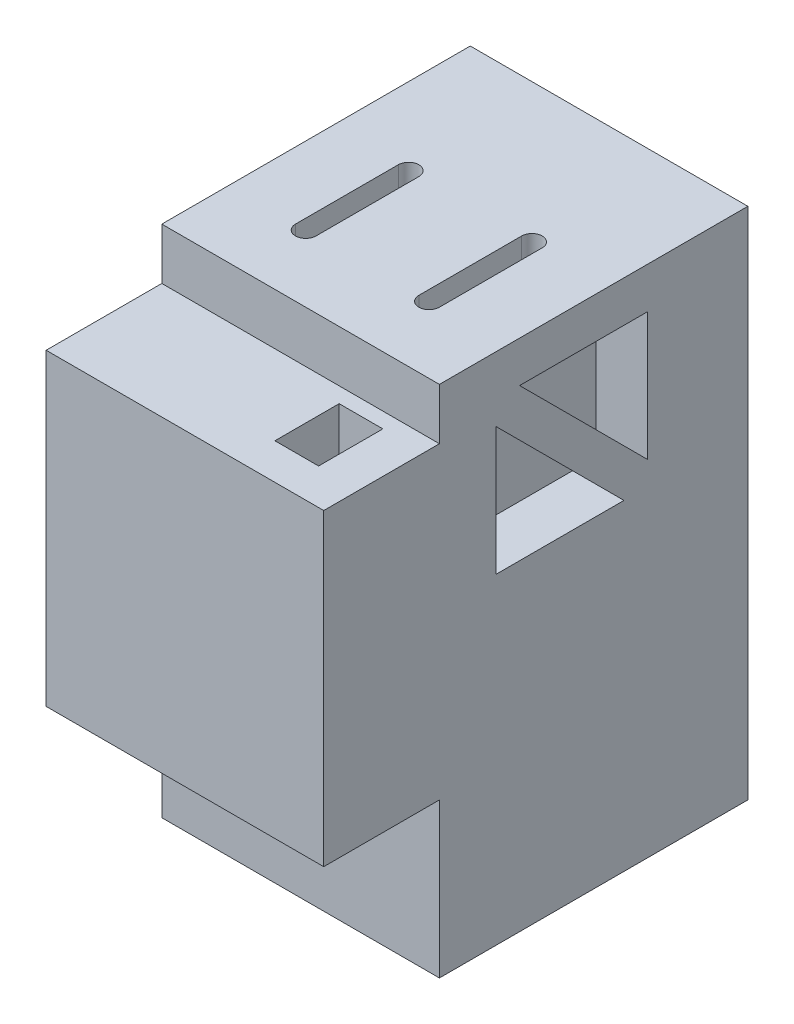
SolidWorks part; units mm, degrees
ref_plane "前视基准面" through (0, 0, 0) normal (0, 0, 1) x (1, 0, 0)
ref_plane "上视基准面" through (0, 0, 0) normal (0, 1, 0) x (1, 0, 0)
ref_plane "右视基准面" through (0, 0, 0) normal (1, 0, 0) x (0, 0, -1)
sketch "草图1" plane through (0, 0, 0) normal (0, 0, 1) x (1, 0, 0)
  line L0 (-54, 0) -> (0, 0)
  line L1 (0, 0) -> (0, -100)
  line L2 (-54, 0) -> (-54, -100)
  line L3 (-54, -100) -> (0, -100)
  dimension "D1" = 54
  dimension "D2" = 100
extrude "凸台-拉伸1" add sketch "草图1" along normal blind 60
sketch "草图2" plane through (0, 0, 60) normal (0, 0, 1) x (1, 0, 0)
  line L0 (-54, -10) -> (0, -10)
  line L1 (-54, 0) -> (-54, -100) construction
  line L2 (0, -100) -> (0, 0) construction
  line L3 (0, -10) -> (0, -70)
  line L4 (0, -70) -> (-54, -70)
  line L5 (-54, -70) -> (-54, -10)
  line L6 (0, 0) -> (-54, 0) construction
  dimension "D1" = 10
  dimension "D2" = 60
extrude "凸台-拉伸2" add sketch "草图2" along normal blind 22.5
sketch "草图3" plane through (0, -10, 0) normal (0, 1, 0) x (1, 0, 0)
  line L0 (0, -82.5) -> (0, -60) construction
  line L1 (-16.5, -75.5) -> (-8, -75.5)
  line L2 (-16.5, -75.5) -> (-16.5, -63)
  line L3 (-16.5, -63) -> (-8, -63)
  line L4 (-8, -75.5) -> (-8, -63)
  line L5 (-16.5, -75.5) -> (-8, -63) construction
  line L6 (-16.5, -63) -> (-8, -75.5) construction
  line L7 (0, -60) -> (-54, -60) construction
  line L8 (0, -82.5) -> (-54, -82.5) construction
  point P0 (-12.25, -69.25)
  dimension "D1" = 8.5
  dimension "D2" = 8
  dimension "D3" = 12.5
  dimension "D4" = 3
  dimension "D5" = 7
extrude "切除-拉伸1" cut sketch "草图3" against normal blind 22.5
sketch "草图4" plane through (0, 0, 0) normal (0, 1, 0) x (1, 0, 0)
  line L0 (-39, -27) -> (-39, -47) construction
  line L1 (-37, -27) -> (-37, -47)
  line L2 (-41, -27) -> (-41, -47)
  line L3 (-27, 0) -> (-27, -60) construction
  line L4 (0, 0) -> (-54, 0) construction
  line L5 (0, -60) -> (-54, -60) construction
  line L6 (-15, -27) -> (-15, -47) construction
  line L7 (-17, -27) -> (-17, -47)
  line L8 (-13, -27) -> (-13, -47)
  line L9 (0, -60) -> (0, 0) construction
  line L10 (-39, -25) -> (-39, -27) construction
  line L11 (-39, -49) -> (-39, -47) construction
  line L12 (0, -60) -> (-54, -60) construction
  arc A0 (-37, -27) -> (-41, -27) centre (-39, -27) ccw
  arc A1 (-41, -47) -> (-37, -47) centre (-39, -47) ccw
  arc A2 (-17, -27) -> (-13, -27) centre (-15, -27) cw
  arc A3 (-13, -47) -> (-17, -47) centre (-15, -47) cw
  point P2 (-39, -37)
  point P15 (-15, -37)
  dimension "D4" = 24
  dimension "D1" = 4
  dimension "D2" = 20
  dimension "D3" = 13
  dimension "D5" = 11
extrude "切除-拉伸2" cut sketch "草图4" against normal blind 10
sketch "草图5" plane through (0, 0, 0) normal (1, 0, 0) x (0, 0, -1)
  line L0 (-44.4038, -8) -> (-19.5, -8)
  line L1 (-19.5, -8) -> (-19.5, -32.9038)
  line L2 (-19.5, -32.9038) -> (-44.4038, -8)
  line L3 (-21.7981, -35.2019) -> (-46.7019, -10.2981) construction
  line L4 (-24.0962, -37.5) -> (-49, -12.5962)
  line L5 (-49, -37.5) -> (-24.0962, -37.5)
  line L6 (-49, -12.5962) -> (-49, -37.5)
  line L7 (-60, 0) -> (0, 0) construction
  line L8 (-60, -10) -> (-60, 0) construction
  line L9 (0, -100) -> (0, 0) construction
  dimension "D2" = 29.5
  dimension "D1" = 6.5
  dimension "D3" = 8
  dimension "D4" = 11
  dimension "D5" = 19.5
extrude "切除-拉伸3" cut sketch "草图5" against normal blind 10
